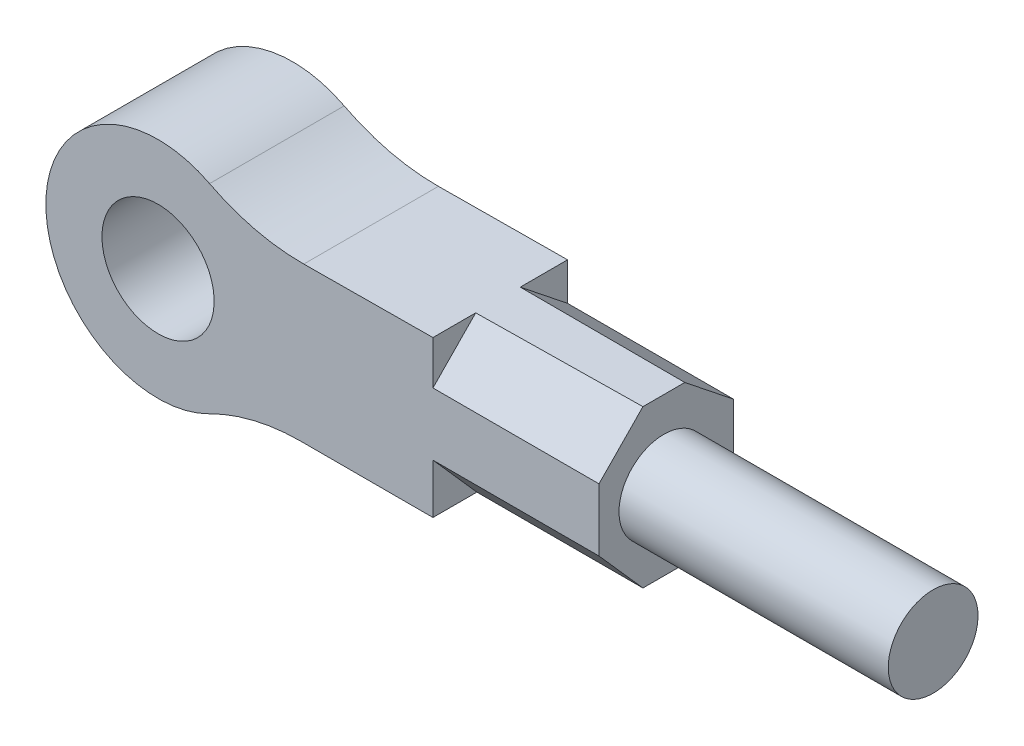
SolidWorks part; units mm, degrees
ref_plane "Front Plane" through (0, 0, 0) normal (0, 0, 1) x (1, 0, 0)
ref_plane "Top Plane" through (0, 0, 0) normal (0, 1, 0) x (1, 0, 0)
ref_plane "Right Plane" through (0, 0, 0) normal (1, 0, 0) x (0, 0, -1)
sketch "Sketch1" plane through (0, 0, 0) normal (0, 0, 1) x (1, 0, 0)
  line L0 (-87.7946, -0.7105) -> (227.0931, 0.437) construction
  line L2 (64.9475, 34.3671) -> (196.5074, 35.326)
  line L3 (36.5117, -34.1599) -> (36.5117, -34.674)
  line L4 (63.6899, -34.674) -> (196.5117, -34.674)
  line L5 (196.5074, 35.326) -> (196.5117, -34.674)
  arc A0 (22.9613, 44.416) -> (22.7464, -44.5264) centre (0, 0) ccw
  circle A1 centre (0, 0) radius 25
  arc A2 (64.9475, 34.3671) -> (22.9613, 44.416) centre (64.2916, 124.3648) cw
  arc A3 (22.7464, -44.5264) -> (63.6899, -34.674) centre (63.6899, -124.674) cw
  point P11 (36.5117, 34.1599)
  dimension "D1" = 100
  dimension "D2" = 50
  dimension "D5" = 90
  dimension "D3" = 160
  dimension "D4" = 70
extrude "Boss-Extrude1" add sketch "Sketch1" along normal blind 60
sketch "Sketch2" plane through (196.5096, 0.0119, 0) normal (1, 0.0001, 0) x (0, 0, -1)
  line L0 (-21.7596, 35.3141) -> (0, 17.9746)
  line L1 (-40.4197, 35.3141) -> (-60, 15.3141)
  line L2 (-60, -12.5353) -> (-40.4197, -34.6859)
  line L3 (-18.4907, -34.6859) -> (0, -16.1952)
  circle A0 centre (-30, 0) radius 25
  line M2 (0, -34.6859) -> (0, 35.3141)
  line M3 (0, 35.3141) -> (-60, 35.3141)
  line M4 (-60, 35.3141) -> (-60, -34.6859)
  line M5 (-60, -34.6859) -> (0, -34.6859)
  dimension "D1" = 50
extrude "Cut-Extrude1" cut sketch "Sketch2" against normal blind 74 contours L1 M3 M4 | L0 M3 M2 | L2 M4 M5 | L3 M5 M2
sketch "Sketch3" plane through (196.5096, 0.0119, 0) normal (1, 0.0001, 0) x (0, 0, -1)
  circle A0 centre (-31.0896, 0) radius 20
  dimension "D1" = 40
extrude "Boss-Extrude2" add sketch "Sketch3" along normal blind 120
